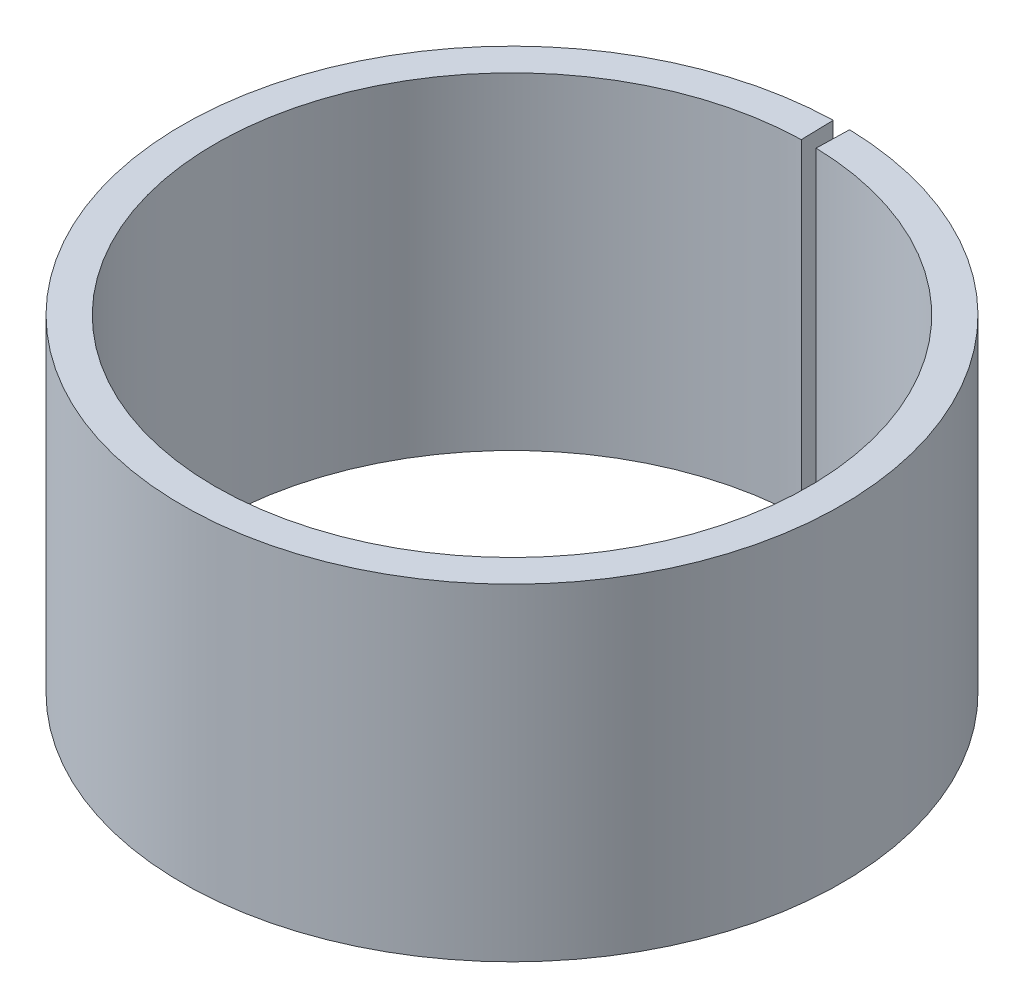
SolidWorks part; units mm, degrees
material "ABS"
ref_plane "Front Plane" through (0, 0, 0) normal (0, 0, 1) x (1, 0, 0)
ref_plane "Top Plane" through (0, 0, 0) normal (0, 1, 0) x (1, 0, 0)
ref_plane "Right Plane" through (0, 0, 0) normal (1, 0, 0) x (0, 0, -1)
sketch "Sketch1" plane through (0, 0, 0) normal (0, 1, 0) x (1, 0, 0)
  line L0 (0, 0) -> (0, 51.1652) construction
  line L1 (1.1439, 46.0868) -> (1.27, 51.1652)
  line L2 (-1.1439, 46.0868) -> (-1.27, 51.1652)
  line L3 (-1.1439, 46.0868) -> (0, 0) construction
  line L4 (0, 0) -> (1.1439, 46.0868) construction
  arc A0 (-1.27, 51.1652) -> (1.27, 51.1652) centre (0, 0) ccw
  arc A1 (-1.1439, 46.0868) -> (1.1439, 46.0868) centre (0, 0) ccw
  dimension "D1" = 102.362
  dimension "D2" = 5.08
  dimension "D3" = 2.54
extrude "Boss-Extrude1" add sketch "Sketch1" along normal blind 50.8
